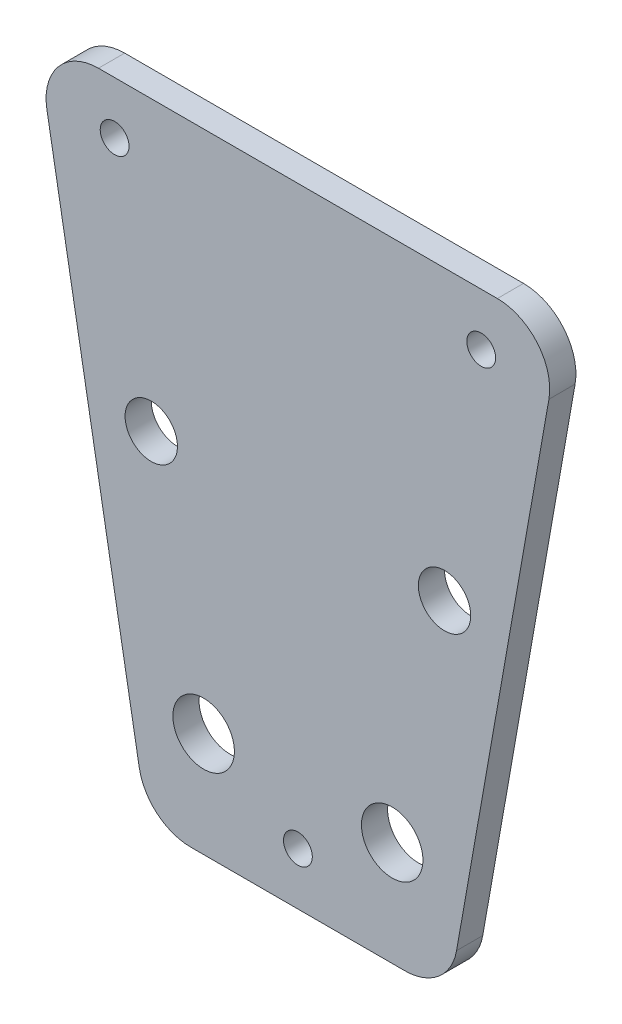
SolidWorks part; units mm, degrees
ref_plane "Front Plane" through (0, 0, 0) normal (0, 0, 1) x (1, 0, 0)
ref_plane "Top Plane" through (0, 0, 0) normal (0, 1, 0) x (1, 0, 0)
ref_plane "Right Plane" through (0, 0, 0) normal (1, 0, 0) x (0, 0, -1)
sketch "Sketch1" plane through (0, 0, 0) normal (0, 0, 1) x (1, 0, 0)
  line L0 (-20.449, 0) -> (20.449, 0)
  line L1 (30.2971, 8.2635) -> (47.9298, 108.2635)
  line L2 (38.0817, 120) -> (-38.0817, 120)
  line L3 (0, 0) -> (0, 120) construction
  line L4 (-30.2971, 8.2635) -> (-47.9298, 108.2635)
  arc A0 (20.449, 0) -> (30.2971, 8.2635) centre (20.449, 10) ccw
  arc A1 (47.9298, 108.2635) -> (38.0817, 120) centre (38.0817, 110) ccw
  circle A3 centre (28, 65) radius 5
  circle A4 centre (18, 20) radius 5.8735
  circle A5 centre (0, 10) radius 2.75
  circle A6 centre (35, 110) radius 2.75
  arc A7 (-20.449, 0) -> (-30.2971, 8.2635) centre (-20.449, 10) cw
  arc A8 (-47.9298, 108.2635) -> (-38.0817, 120) centre (-38.0817, 110) cw
  circle A9 centre (-18, 20) radius 5.8735
  circle A10 centre (-28, 65) radius 5
  circle A11 centre (-35, 110) radius 2.75
  point P7 (28.84, 0)
  dimension "D4" = 10
  dimension "D5" = 5.5
  dimension "D6" = 5.5
  dimension "D7" = 10
  dimension "D8" = 11.747
  dimension "D1" = 120
  dimension "D2" = 28.84
  dimension "D3" = 80
  dimension "D9" = 35
  dimension "D10" = 28
  dimension "D11" = 18
  dimension "D12" = 10
  dimension "D13" = 20
  dimension "D14" = 65
extrude "Boss-Extrude1" add sketch "Sketch1" along normal mid plane 5
